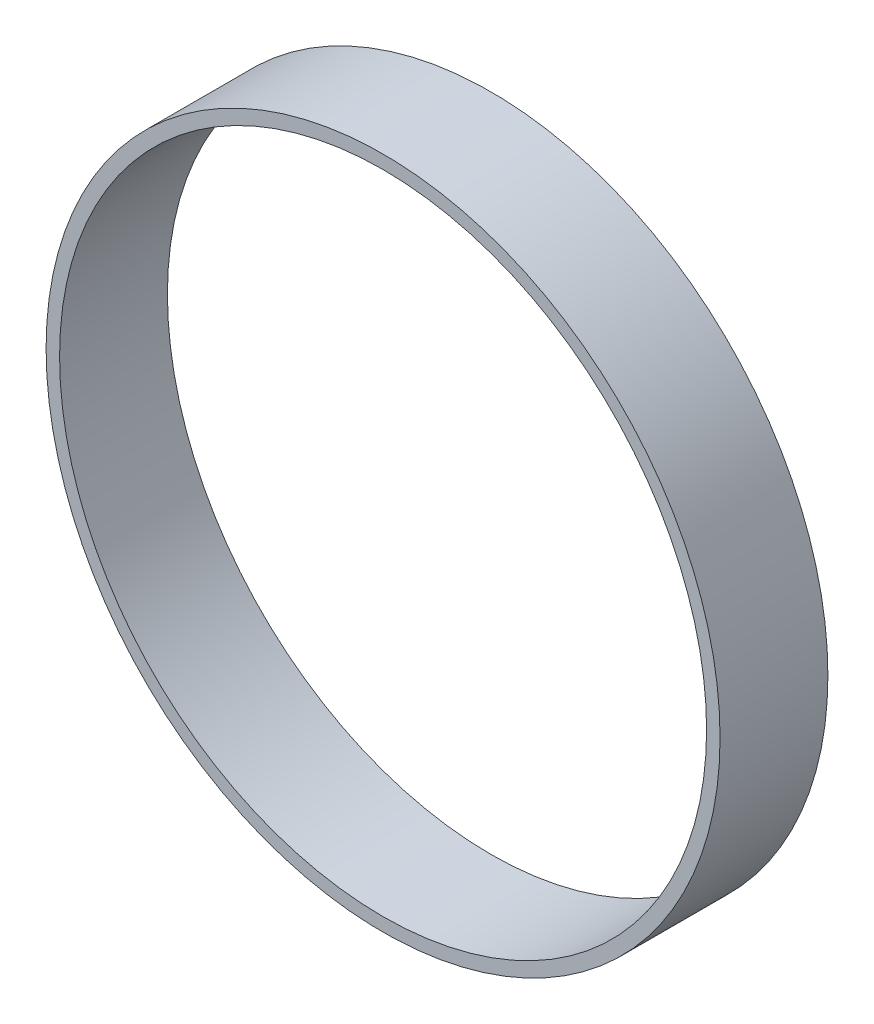
SolidWorks part; units mm, degrees
ref_plane "Front Plane" through (0, 0, 0) normal (0, 0, 1) x (1, 0, 0)
ref_plane "Top Plane" through (0, 0, 0) normal (0, 1, 0) x (1, 0, 0)
ref_plane "Right Plane" through (0, 0, 0) normal (1, 0, 0) x (0, 0, -1)
sketch "Sketch1" plane through (0, 0, 0) normal (1, 0, 0) x (0, 0, -1)
  line L0 (-12.5905, 0) -> (-57.0405, 0) construction
  line L1 (-88.9, 158.75) -> (-38.1, 158.75)
  line L2 (-88.9, 158.75) -> (-88.9, 152.4)
  line L3 (-88.9, 152.4) -> (-38.1, 152.4)
  line L4 (-38.1, 158.75) -> (-38.1, 152.4)
  dimension "D1" = 6.35
  dimension "D2" = 50.8
  dimension "D3" = 38.1
  dimension "D4" = 304.8
revolve "Revolve1" add sketch "Sketch1" angle 360 about L0
